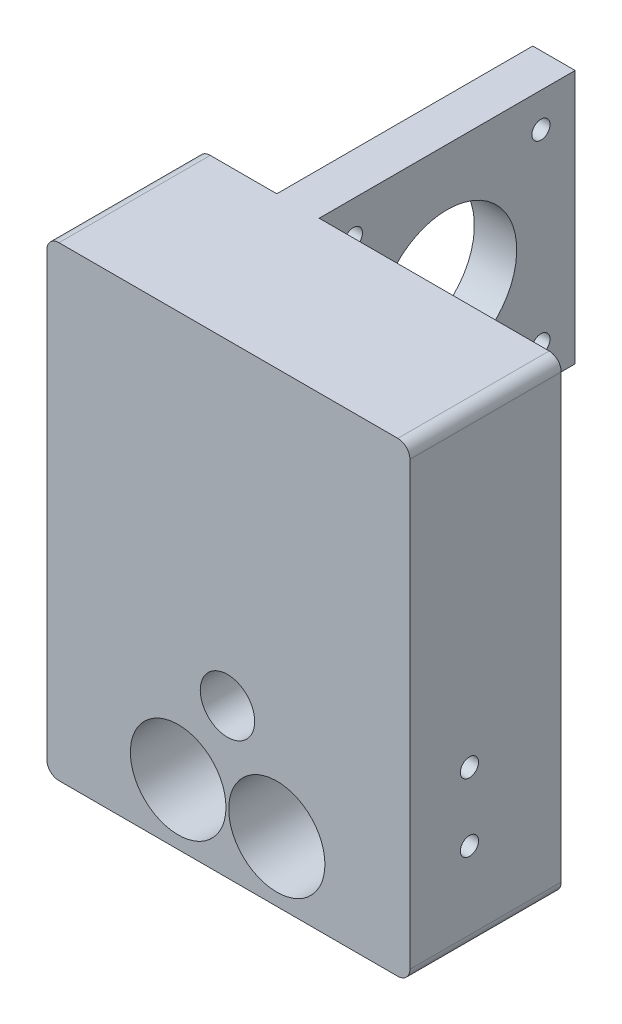
SolidWorks part; units mm, degrees
ref_plane "Plan de face" through (0, 0, 0) normal (0, 0, 1) x (1, 0, 0)
ref_plane "Plan de dessus" through (0, 0, 0) normal (0, 1, 0) x (1, 0, 0)
ref_plane "Plan de droite" through (0, 0, 0) normal (1, 0, 0) x (0, 0, -1)
sketch "Esquisse1" plane through (0, 0, 0) normal (0, 0, 1) x (1, 0, 0)
  line L1 (0, 0) -> (100, 0)
  line L2 (0, 0) -> (0, 100)
  line L3 (0, 100) -> (100, 100)
  line L4 (100, 0) -> (100, 100)
  dimension "D1" = 100
  dimension "D2" = 100
extrude "Boss.-Extru.1" add sketch "Esquisse1" along normal blind 25
sketch "Esquisse2" plane through (0, 0, 0) normal (0, 0, 1) x (1, 0, 0)
  line L1 (100, 0) -> (100, 100) construction
  line L2 (0, 0) -> (100, 0) construction
  circle A0 centre (61.7, 9.9946) radius 7.9
  circle A1 centre (78, 10) radius 7.95
  circle A2 centre (69.8451, 24.6423) radius 4.5
  dimension "D1" = 9
  dimension "D2" = 15.9
  dimension "D3" = 15.8
  dimension "D7" = 10
  dimension "D4" = 16.3
  dimension "D5" = 16.76
  dimension "D6" = 16.76
  dimension "D8" = 22
extrude "Enlèv. mat.-Extru.1" cut sketch "Esquisse2" along normal through all
sketch "Esquisse3" plane through (0, 0, 0) normal (0, 1, 0) x (1, 0, 0)
  line L1 (100, -25) -> (100, 0) construction
  line L2 (0, 0) -> (100, 0) construction
  circle A0 centre (48, -12.5) radius 4.3
  circle A1 centre (92, -12.5) radius 4.3
  dimension "D1" = 8.6
  dimension "D2" = 8.6
  dimension "D4" = 8
  dimension "D6" = 12.5
  dimension "D3" = 44
  dimension "D5" = 12.5
extrude "Enlèv. mat.-Extru.3" cut sketch "Esquisse3" along normal blind 10
sketch "Esquisse4" plane through (0, 0, 0) normal (0, 0, 1) x (1, 0, 0)
  line L0 (100, 0) -> (100, 100) construction
  line L1 (60, 77) -> (53, 77)
  line L2 (60, 77) -> (60, 35)
  line L3 (60, 35) -> (53, 35)
  line L4 (53, 77) -> (53, 35)
  line L5 (0, 0) -> (100, 0) construction
  point P4 (56.5, 77)
  dimension "D1" = 3.5
  dimension "D2" = 42
  dimension "D3" = 40
  dimension "D4" = 35
extrude "Boss.-Extru.2" add sketch "Esquisse4" against normal blind 42.3
sketch "Esquisse5" plane through (60, 0, 0) normal (1, 0, 0) x (0, 0, -1)
  line L0 (0, 0) -> (0, 100) construction
  line L1 (42.3, 35) -> (0, 35) construction
  line L2 (42.3, 77) -> (0, 77) construction
  line L4 (42.3, 35) -> (42.3, 77) construction
  line L5 (0, 0) -> (0, 100) construction
  circle A0 centre (36.65, 71.35) radius 1.5
  circle A1 centre (36.65, 40.65) radius 1.5
  circle A2 centre (5.65, 40.65) radius 1.5
  circle A3 centre (5.65, 71.35) radius 1.5
  dimension "D1" = 3
  dimension "D2" = 3
  dimension "D3" = 3
  dimension "D4" = 3
  dimension "D5" = 5.65
  dimension "D6" = 5.65
  dimension "D7" = 5.65
  dimension "D8" = 5.65
  dimension "D9" = 5.65
  dimension "D10" = 5.65
  dimension "D11" = 5.65
  dimension "D12" = 5.65
extrude "Enlèv. mat.-Extru.4" cut sketch "Esquisse5" against normal blind 12
sketch "Esquisse6" plane through (0, 0, 0) normal (0, 0, 1) x (1, 0, 0)
  line L0 (0, 0) -> (100, 0) construction
  line L1 (40, 0) -> (0, 0)
  line L2 (40, 0) -> (40, 100)
  line L3 (40, 100) -> (0, 100)
  line L4 (0, 0) -> (0, 100)
  dimension "D1" = 40
extrude "Enlèv. mat.-Extru.6" cut sketch "Esquisse6" along normal through all
sketch "Esquisse8" plane through (0, 0, 0) normal (0, 0, -1) x (-1, 0, 0)
  line L1 (-62.691, 21.8527) -> (-63.8522, 29.4431)
  line L2 (-63.8522, 29.4431) -> (-71.0064, 32.2327)
  line L3 (-71.0064, 32.2327) -> (-76.9993, 27.4318)
  line L4 (-76.9993, 27.4318) -> (-75.838, 19.8414)
  line L5 (-75.838, 19.8414) -> (-68.6839, 17.0518)
  line L6 (-68.6839, 17.0518) -> (-62.691, 21.8527)
  circle A0 centre (-69.8451, 24.6423) radius 6.65 construction
  dimension "D1" = 13.3
extrude "Enlèv. mat.-Extru.8" cut sketch "Esquisse8" against normal blind 7.5
sketch "Esquisse10" plane through (53, 0, 0) normal (-1, 0, 0) x (0, 0, 1)
  line L0 (-42.3, 77) -> (-42.3, 35) construction
  line L1 (-42.3, 35) -> (0, 35) construction
  circle A0 centre (-21.15, 56.15) radius 11.5
  dimension "D1" = 21.15
  dimension "D2" = 21.15
  dimension "D3" = 23
extrude "Enlèv. mat.-Extru.10" cut sketch "Esquisse10" against normal through all
sketch "Esquisse11" plane through (100, 0, 0) normal (1, 0, 0) x (0, 0, -1)
  circle A0 centre (-15.164, 26) radius 1.5
  circle A1 centre (-15.164, 14.7519) radius 1.5
  dimension "D1" = 3
  dimension "D2" = 3
extrude "Enlèv. mat.-Extru.11" cut sketch "Esquisse11" against normal blind 3
sketch "Esquisse12" plane through (0, 0, 0) normal (0, 0, -1) x (-1, 0, 0)
  line L0 (-40, 0) -> (-40, 100) construction
  line L1 (-100, 100) -> (-40, 100)
  line L2 (-100, 100) -> (-100, 77)
  line L3 (-100, 77) -> (-40, 77)
  line L4 (-40, 100) -> (-40, 77)
  line L7 (-60, 77) -> (-53, 77) construction
extrude "Enlèv. mat.-Extru.12" cut sketch "Esquisse12" against normal through all
fillet "Congé1" radius 2 4 edges at (100, 77, 12.5) (40, 77, 12.5) (40, 0, 12.5) (100, 0, 12.5)
